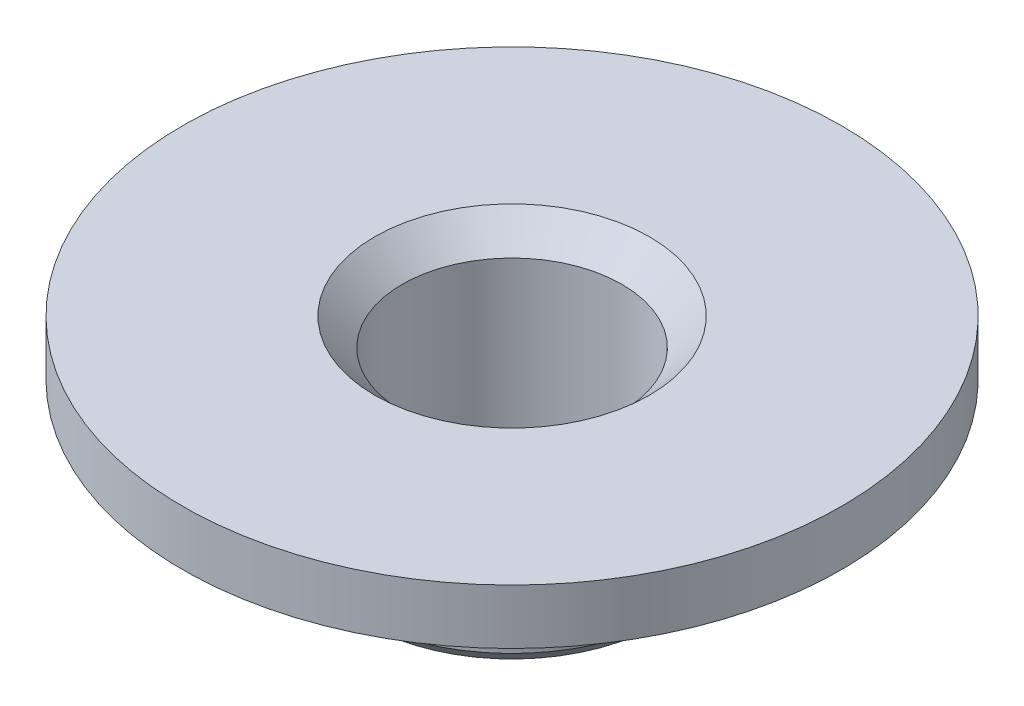
SolidWorks part; units mm, degrees
ref_plane "Plan de face" through (0, 0, 0) normal (0, 0, 1) x (1, 0, 0)
ref_plane "Plan de dessus" through (0, 0, 0) normal (0, 1, 0) x (1, 0, 0)
ref_plane "Plan de droite" through (0, 0, 0) normal (1, 0, 0) x (0, 0, -1)
sketch "Esquisse1" plane through (0, 0, 0) normal (0, 0, 1) x (1, 0, 0)
  line L0 (0, 0) -> (0, 6.8073) construction
  line L1 (2, 0) -> (2, 3.5)
  line L2 (2, 3.5) -> (6, 3.5)
  line L3 (6, 3.5) -> (6, 2.5)
  line L4 (6, 2.5) -> (4.25, 2.5)
  line L5 (4.25, 2.5) -> (4.25, 1.7245)
  line L6 (4.25, 1.7245) -> (3, 1.7245)
  line L7 (3, 1.7245) -> (3, 0)
  line L8 (3, 0) -> (2, 0)
  dimension "D1" = 4
  dimension "D2" = 1
  dimension "D3" = 6
  dimension "D4" = 12
  dimension "D5" = 8.5
  dimension "D6" = 2.5
revolve "Révolution1" add sketch "Esquisse1" angle 360 about L0
chamfer "Chanfrein1" distance 0.5 angle 45 1 edges at (0, 3.5, -2)
chamfer "Chanfrein2" distance 0.3 angle 45 2 edges at (0, 1.7245, -4.25) (0, 0, -3)
